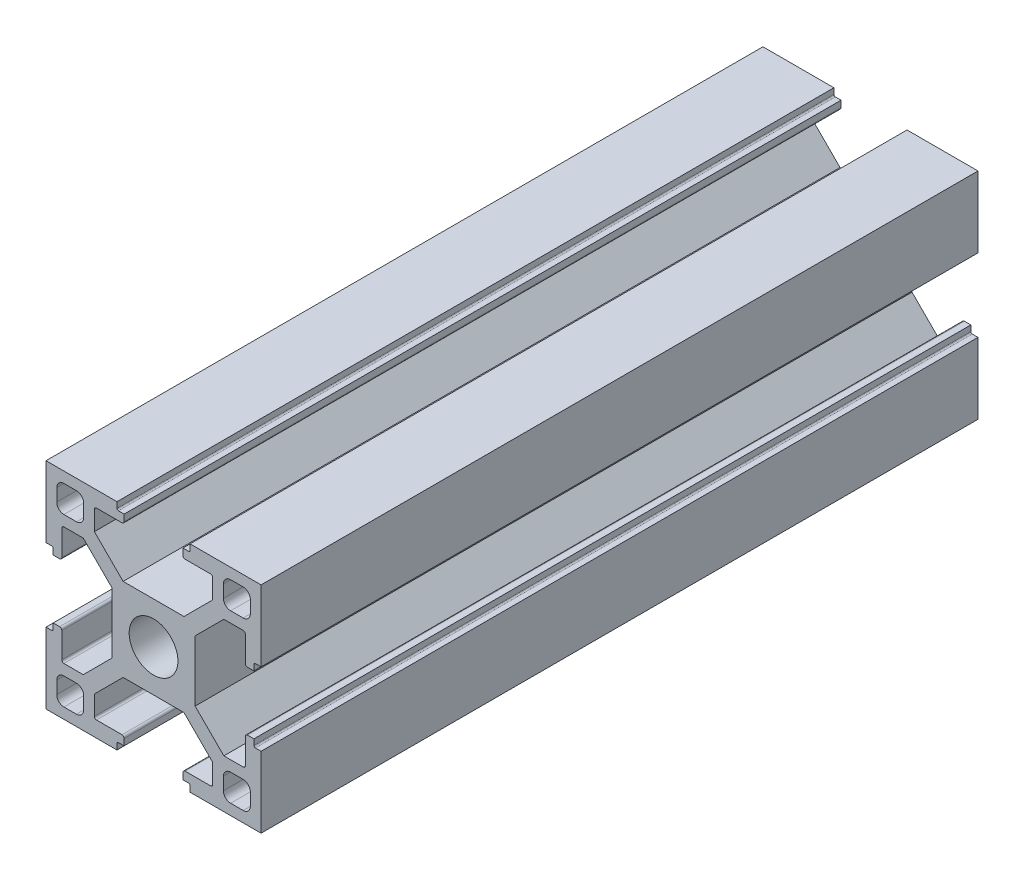
SolidWorks part; units mm, degrees
ref_plane "前视基准面" through (0, 0, 0) normal (0, 0, 1) x (1, 0, 0)
ref_plane "上视基准面" through (0, 0, 0) normal (0, 1, 0) x (1, 0, 0)
ref_plane "右视基准面" through (0, 0, 0) normal (1, 0, 0) x (0, 0, -1)
sketch "草图1" plane through (0, 0, 0) normal (0, 0, 1) x (1, 0, 0)
  line L0 (2.326, -15.244) -> (4.076, -15.244)
  line L1 (5.076, -16.244) -> (5.076, -17.994)
  line L2 (4.076, -18.994) -> (2.326, -18.994)
  line L3 (1.326, -17.994) -> (1.326, -16.244)
  line L4 (1.326, 5.256) -> (1.326, 7.006)
  line L5 (2.326, 8.006) -> (4.076, 8.006)
  line L6 (5.076, 7.006) -> (5.076, 5.256)
  line L7 (4.076, 4.256) -> (2.326, 4.256)
  line L8 (-18.174, -16.244) -> (-18.174, -17.994)
  line L9 (-19.174, -18.994) -> (-20.924, -18.994)
  line L10 (-21.924, -17.994) -> (-21.924, -16.244)
  line L11 (-20.924, -15.244) -> (-19.174, -15.244)
  line L12 (-19.174, 4.256) -> (-20.924, 4.256)
  line L13 (-21.924, 5.256) -> (-21.924, 7.006)
  line L14 (-20.924, 8.006) -> (-19.174, 8.006)
  line L15 (-18.174, 7.006) -> (-18.174, 5.256)
  line L16 (-23.424, 7.006) -> (-23.424, -0.394)
  line L17 (-23.424, -0.394) -> (-22.624, -0.394)
  line L18 (-22.424, -0.594) -> (-22.424, -1.394)
  line L19 (-22.424, -1.394) -> (-21.524, -1.394)
  line L20 (-21.224, -1.094) -> (-21.224, 2.456)
  line L21 (-20.924, 2.756) -> (-18.2297, 2.756)
  line L22 (-18.2297, 2.756) -> (-14.224, -1.2497)
  line L23 (-14.224, -1.2497) -> (-14.224, -9.7384)
  line L24 (-14.224, -9.7384) -> (-18.2297, -13.744)
  line L25 (-18.2297, -13.744) -> (-20.924, -13.744)
  line L26 (-21.224, -13.444) -> (-21.224, -9.894)
  line L27 (-21.524, -9.594) -> (-22.424, -9.594)
  line L28 (-22.424, -9.594) -> (-22.424, -10.394)
  line L29 (-22.624, -10.594) -> (-23.424, -10.594)
  line L30 (-23.424, -10.594) -> (-23.424, -17.994)
  line L31 (-20.924, -20.494) -> (-13.524, -20.494)
  line L32 (-13.524, -20.494) -> (-13.524, -19.694)
  line L33 (-13.324, -19.494) -> (-12.524, -19.494)
  line L34 (-12.524, -19.494) -> (-12.524, -18.594)
  line L35 (-12.824, -18.294) -> (-16.374, -18.294)
  line L36 (-16.674, -17.994) -> (-16.674, -15.2997)
  line L37 (-16.674, -15.2997) -> (-12.6684, -11.294)
  line L38 (-12.6684, -11.294) -> (-4.1797, -11.294)
  line L39 (-4.1797, -11.294) -> (-0.174, -15.2997)
  line L40 (-0.174, -15.2997) -> (-0.174, -17.994)
  line L41 (-0.474, -18.294) -> (-4.024, -18.294)
  line L42 (-4.324, -18.594) -> (-4.324, -19.494)
  line L43 (-4.324, -19.494) -> (-3.524, -19.494)
  line L44 (-3.324, -19.694) -> (-3.324, -20.494)
  line L45 (-3.324, -20.494) -> (4.076, -20.494)
  line L46 (6.576, -17.994) -> (6.576, -10.594)
  line L47 (6.576, -10.594) -> (5.776, -10.594)
  line L48 (5.576, -10.394) -> (5.576, -9.594)
  line L49 (5.576, -9.594) -> (4.676, -9.594)
  line L50 (4.376, -9.894) -> (4.376, -13.444)
  line L51 (4.076, -13.744) -> (1.3816, -13.744)
  line L52 (1.3816, -13.744) -> (-2.624, -9.7384)
  line L53 (-2.624, -9.7384) -> (-2.624, -1.2497)
  line L54 (-2.624, -1.2497) -> (1.3816, 2.756)
  line L55 (1.3816, 2.756) -> (4.076, 2.756)
  line L56 (4.376, 2.456) -> (4.376, -1.094)
  line L57 (4.676, -1.394) -> (5.576, -1.394)
  line L58 (5.576, -1.394) -> (5.576, -0.594)
  line L59 (5.776, -0.394) -> (6.576, -0.394)
  line L60 (6.576, -0.394) -> (6.576, 7.006)
  line L61 (4.076, 9.506) -> (-3.324, 9.506)
  line L62 (-3.324, 9.506) -> (-3.324, 8.706)
  line L63 (-3.524, 8.506) -> (-4.324, 8.506)
  line L64 (-4.324, 8.506) -> (-4.324, 7.606)
  line L65 (-4.024, 7.306) -> (-0.474, 7.306)
  line L66 (-0.174, 7.006) -> (-0.174, 4.3116)
  line L67 (-0.174, 4.3116) -> (-4.1797, 0.306)
  line L68 (-4.1797, 0.306) -> (-12.6684, 0.306)
  line L69 (-12.6684, 0.306) -> (-16.674, 4.3116)
  line L70 (-16.674, 4.3116) -> (-16.674, 7.006)
  line L71 (-16.374, 7.306) -> (-12.824, 7.306)
  line L72 (-12.524, 7.606) -> (-12.524, 8.506)
  line L73 (-12.524, 8.506) -> (-13.324, 8.506)
  line L74 (-13.524, 8.706) -> (-13.524, 9.506)
  line L75 (-13.524, 9.506) -> (-20.924, 9.506)
  line L76 (-20.924, 9.506) -> (-23.424, 9.506)
  line L77 (-23.424, 9.506) -> (-23.424, 7.006)
  line L78 (4.076, 9.506) -> (6.576, 9.506)
  line L79 (6.576, 9.506) -> (6.576, 7.006)
  line L80 (-20.924, -20.494) -> (-23.424, -20.494)
  line L81 (-23.424, -20.494) -> (-23.424, -17.994)
  line L82 (4.076, -20.494) -> (6.576, -20.494)
  line L83 (6.576, -20.494) -> (6.576, -17.994)
  arc A0 (5.076, -16.244) -> (4.076, -15.244) centre (4.076, -16.244) ccw
  arc A1 (4.076, -18.994) -> (5.076, -17.994) centre (4.076, -17.994) ccw
  arc A2 (1.326, -17.994) -> (2.326, -18.994) centre (2.326, -17.994) ccw
  arc A3 (2.326, -15.244) -> (1.326, -16.244) centre (2.326, -16.244) ccw
  arc A4 (2.326, 8.006) -> (1.326, 7.006) centre (2.326, 7.006) ccw
  arc A5 (5.076, 7.006) -> (4.076, 8.006) centre (4.076, 7.006) ccw
  arc A6 (4.076, 4.256) -> (5.076, 5.256) centre (4.076, 5.256) ccw
  arc A7 (1.326, 5.256) -> (2.326, 4.256) centre (2.326, 5.256) ccw
  arc A8 (-19.174, -18.994) -> (-18.174, -17.994) centre (-19.174, -17.994) ccw
  arc A9 (-21.924, -17.994) -> (-20.924, -18.994) centre (-20.924, -17.994) ccw
  arc A10 (-20.924, -15.244) -> (-21.924, -16.244) centre (-20.924, -16.244) ccw
  arc A11 (-18.174, -16.244) -> (-19.174, -15.244) centre (-19.174, -16.244) ccw
  arc A12 (-21.924, 5.256) -> (-20.924, 4.256) centre (-20.924, 5.256) ccw
  arc A13 (-20.924, 8.006) -> (-21.924, 7.006) centre (-20.924, 7.006) ccw
  arc A14 (-18.174, 7.006) -> (-19.174, 8.006) centre (-19.174, 7.006) ccw
  arc A15 (-19.174, 4.256) -> (-18.174, 5.256) centre (-19.174, 5.256) ccw
  circle A16 centre (-8.424, -5.494) radius 3.4
  arc A17 (-22.424, -0.594) -> (-22.624, -0.394) centre (-22.624, -0.594) ccw
  arc A18 (-21.524, -1.394) -> (-21.224, -1.094) centre (-21.524, -1.094) ccw
  arc A19 (-20.924, 2.756) -> (-21.224, 2.456) centre (-20.924, 2.456) ccw
  arc A20 (-21.224, -13.444) -> (-20.924, -13.744) centre (-20.924, -13.444) ccw
  arc A21 (-21.224, -9.894) -> (-21.524, -9.594) centre (-21.524, -9.894) ccw
  arc A22 (-22.624, -10.594) -> (-22.424, -10.394) centre (-22.624, -10.394) ccw
  arc A23 (-13.324, -19.494) -> (-13.524, -19.694) centre (-13.324, -19.694) ccw
  arc A24 (-12.524, -18.594) -> (-12.824, -18.294) centre (-12.824, -18.594) ccw
  arc A25 (-16.674, -17.994) -> (-16.374, -18.294) centre (-16.374, -17.994) ccw
  arc A26 (-0.474, -18.294) -> (-0.174, -17.994) centre (-0.474, -17.994) ccw
  arc A27 (-4.024, -18.294) -> (-4.324, -18.594) centre (-4.024, -18.594) ccw
  arc A28 (-3.324, -19.694) -> (-3.524, -19.494) centre (-3.524, -19.694) ccw
  arc A29 (5.576, -10.394) -> (5.776, -10.594) centre (5.776, -10.394) ccw
  arc A30 (4.676, -9.594) -> (4.376, -9.894) centre (4.676, -9.894) ccw
  arc A31 (4.076, -13.744) -> (4.376, -13.444) centre (4.076, -13.444) ccw
  arc A32 (4.376, 2.456) -> (4.076, 2.756) centre (4.076, 2.456) ccw
  arc A33 (4.376, -1.094) -> (4.676, -1.394) centre (4.676, -1.094) ccw
  arc A34 (5.776, -0.394) -> (5.576, -0.594) centre (5.776, -0.594) ccw
  arc A35 (-3.524, 8.506) -> (-3.324, 8.706) centre (-3.524, 8.706) ccw
  arc A36 (-4.324, 7.606) -> (-4.024, 7.306) centre (-4.024, 7.606) ccw
  arc A37 (-0.174, 7.006) -> (-0.474, 7.306) centre (-0.474, 7.006) ccw
  arc A38 (-16.374, 7.306) -> (-16.674, 7.006) centre (-16.374, 7.006) ccw
  arc A39 (-12.824, 7.306) -> (-12.524, 7.606) centre (-12.824, 7.606) ccw
  arc A40 (-13.524, 8.706) -> (-13.324, 8.506) centre (-13.324, 8.706) ccw
extrude "凸台-拉伸1" add sketch "草图1" along normal blind 100
